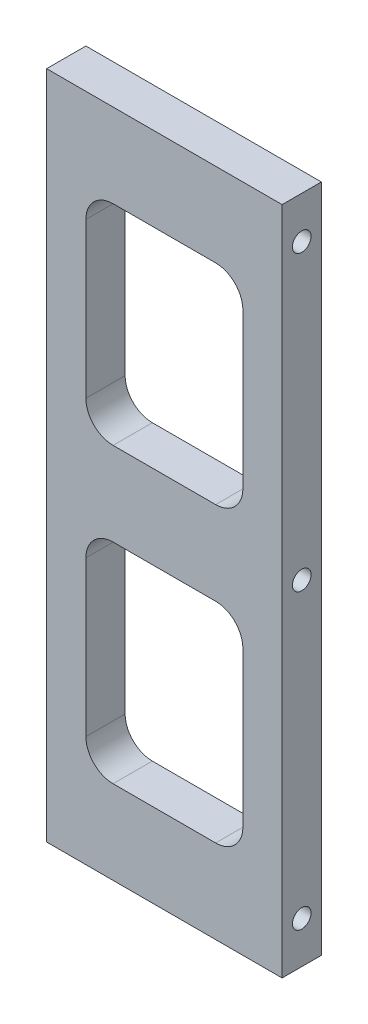
SolidWorks part; units mm, degrees
material "6061-T6 (SS)"
ref_plane "Front Plane" through (0, 0, 0) normal (0, 0, 1) x (1, 0, 0)
ref_plane "Top Plane" through (0, 0, 0) normal (0, 1, 0) x (1, 0, 0)
ref_plane "Right Plane" through (0, 0, 0) normal (1, 0, 0) x (0, 0, -1)
sketch "Sketch1" plane through (0, 0, 0) normal (0, 0, 1) x (1, 0, 0)
  line L1 (-14.2875, -40.64) -> (14.2875, -40.64)
  line L2 (-14.2875, -40.64) -> (-14.2875, 40.64)
  line L3 (-14.2875, 40.64) -> (14.2875, 40.64)
  line L4 (14.2875, -40.64) -> (14.2875, 40.64)
  line L5 (-14.2875, -40.64) -> (14.2875, 40.64) construction
  line L6 (-14.2875, 40.64) -> (14.2875, -40.64) construction
  point P0 (0, 0)
  dimension "D1" = 28.575
  dimension "D2" = 81.28
extrude "Boss-Extrude1" add sketch "Sketch1" along normal blind 4.7625
sketch "Sketch2" plane through (0, 0, 4.7625) normal (0, 0, 1) x (1, 0, 0)
  line L0 (-14.2875, 0) -> (14.2875, 0) construction
  line L1 (-14.2875, 40.64) -> (-14.2875, -40.64) construction
  line L2 (14.2875, -40.64) -> (14.2875, 40.64) construction
  line L3 (0, 40.64) -> (0, 0) construction
  line L4 (14.2875, 40.64) -> (-14.2875, 40.64) construction
  line L5 (-9.525, -30.48) -> (9.525, -5.08) construction
  line L6 (-9.525, 5.08) -> (9.525, 5.08)
  line L7 (-9.525, 5.08) -> (-9.525, 30.48)
  line L8 (-9.525, 30.48) -> (9.525, 30.48)
  line L9 (9.525, 5.08) -> (9.525, 30.48)
  line L10 (-9.525, 5.08) -> (9.525, 30.48) construction
  line L11 (-9.525, 30.48) -> (9.525, 5.08) construction
  line L12 (-9.525, -5.08) -> (9.525, -30.48) construction
  line L13 (9.525, -5.08) -> (9.525, -30.48)
  line L14 (-9.525, -30.48) -> (9.525, -30.48)
  line L15 (-9.525, -5.08) -> (-9.525, -30.48)
  line L16 (-9.525, -5.08) -> (9.525, -5.08)
  point P11 (0, 17.78)
  point P20 (0, -17.78)
  dimension "D1" = 4.7625
  dimension "D2" = 5.08
  dimension "D3" = 10.16
extrude "Cut-Extrude1" cut sketch "Sketch2" against normal through all
fillet "Fillet1" radius 3.302 8 edges at (-9.525, -30.48, 2.3813) (9.525, -30.48, 2.3813) (-9.525, -5.08, 2.3813) (9.525, -5.08, 2.3813) (-9.525, 5.08, 2.3813) (9.525, 5.08, 2.3813) (9.525, 30.48, 2.3813) (-9.525, 30.48, 2.3813)
hole_wizard "#4-40 Tapped Hole1" positions "Sketch4" profile "Sketch5" tap size "#4-40" standard "ANSI Inch" end condition through all
sketch "Sketch4" plane through (14.2875, 0, 0) normal (1, 0, 0) x (0, 0, -1)
  line L0 (-2.3813, 40.64) -> (-2.3813, -40.64) construction
  line L1 (-4.7625, 40.64) -> (0, 40.64) construction
  line L2 (-4.7625, -40.64) -> (0, -40.64) construction
  line L3 (-4.7625, 40.64) -> (0, 40.64) construction
  point P9 (-2.3813, 35.56)
  point P11 (-2.3813, 0)
  point P13 (-2.3813, -35.56)
  dimension "D1" = 5.08
  dimension "D2" = 5.08
sketch "Sketch5" plane through (14.2875, 35.56, 2.3813) normal (0, 1, 0) x (0, 0, -1)
  line L0 (0, 0) -> (0, 28.575)
  line L1 (0, 28.575) -> (1.1303, 28.575)
  line L2 (1.1303, 28.575) -> (1.1303, 0)
  line L5 (1.1303, 0) -> (0, 0)
  line L11 (0, -6.35) -> (0, 107.95) construction
  dimension "Thru Tap Drill Dia." = 2.2606
  dimension "Thru Tap Drill Depth" = 28.575
cosmetic thread "Hole Thread1" parameters "D2"=2.8448
cosmetic thread "Hole Thread2" parameters "D2"=2.8448
cosmetic thread "Hole Thread3" parameters "D2"=2.8448
